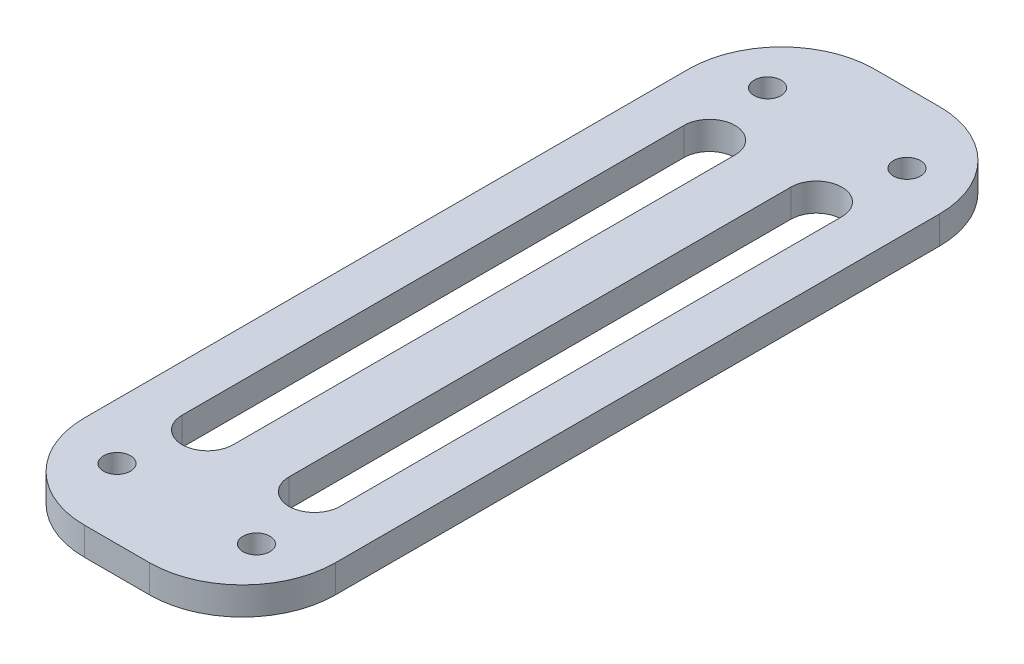
SolidWorks part; units mm, degrees
material "Thornel Mat VMA"
ref_plane "前视基准面" through (0, 0, 0) normal (0, 0, 1) x (1, 0, 0)
ref_plane "上视基准面" through (0, 0, 0) normal (0, 1, 0) x (1, 0, 0)
ref_plane "右视基准面" through (0, 0, 0) normal (1, 0, 0) x (0, 0, -1)
other "Configuration Table"
sketch "草图1" plane through (0, 0, 0) normal (0, 1, 0) x (1, 0, 0)
  line L1 (0, 0) -> (27, 0)
  line L2 (0, 0) -> (0, 85)
  line L3 (0, 85) -> (27, 85)
  line L4 (27, 0) -> (27, 85)
  dimension "D1" = 27
  dimension "D2" = 85
extrude "凸台-拉伸1" add sketch "草图1" along normal blind 3
sketch "草图2" plane through (0, 3, 0) normal (0, 1, 0) x (1, 0, 0)
  line L0 (27, 0) -> (27, 85) construction
  line L1 (0, 85) -> (27, 85) construction
  line L2 (0, 85) -> (0, 70) construction
  line L3 (0, 70) -> (27, 70) construction
  line L4 (27, 85) -> (27, 70) construction
  line L5 (0, 77.5) -> (27, 77.5) construction
  line L6 (0, 0) -> (27, 0) construction
  line L7 (0, 0) -> (0, 15) construction
  line L8 (0, 15) -> (27, 15) construction
  line L9 (27, 0) -> (27, 15) construction
  line L10 (0, 7.5) -> (27, 7.5) construction
  line L11 (13.5, 85) -> (13.5, 0) construction
  line L12 (0, 42.5) -> (27, 42.5) construction
  line L13 (0, 85) -> (0, 0) construction
  circle A2 centre (6, 7.5) radius 1.45
  circle A3 centre (21, 7.5) radius 1.45
  circle A4 centre (21, 77.5) radius 1.45
  circle A5 centre (6, 77.5) radius 1.45
  dimension "D3" = 2.9
  dimension "D4" = 6
  dimension "D1" = 15
  dimension "D2" = 15
extrude "切除-拉伸1" cut sketch "草图2" against normal through all
sketch "草图3" plane through (0, 3, 0) normal (0, 1, 0) x (1, 0, 0)
  line L0 (7.75, 69.5) -> (7.75, 15.5) construction
  line L1 (10.5, 69.5) -> (10.5, 15.5)
  line L2 (5, 69.5) -> (5, 15.5)
  line L3 (13.5, 85) -> (13.5, 0) construction
  line L4 (27, 85) -> (0, 85) construction
  line L5 (0, 0) -> (27, 0) construction
  line L6 (0, 85) -> (0, 0) construction
  line L7 (19.25, 69.5) -> (19.25, 15.5) construction
  line L8 (16.5, 69.5) -> (16.5, 15.5)
  line L9 (22, 69.5) -> (22, 15.5)
  arc A0 (10.5, 69.5) -> (5, 69.5) centre (7.75, 69.5) ccw
  arc A1 (5, 15.5) -> (10.5, 15.5) centre (7.75, 15.5) ccw
  circle A2 centre (6, 77.5) radius 1.45 construction
  circle A3 centre (6, 7.5) radius 1.45 construction
  arc A4 (16.5, 69.5) -> (22, 69.5) centre (19.25, 69.5) cw
  arc A5 (22, 15.5) -> (16.5, 15.5) centre (19.25, 15.5) cw
  point P2 (7.75, 42.5)
  point P13 (6.8462, 70.9997)
  point P14 (7.3847, 13.0772)
  point P23 (19.25, 42.5)
  dimension "D1" = 8
  dimension "D2" = 8
  dimension "D3" = 5
  dimension "D4" = 3
extrude "切除-拉伸2" cut sketch "草图3" against normal through all
fillet "圆角1" radius 10 4 edges at (0, 1.5, -85) (0, 1.5, 0) (27, 1.5, 0) (27, 1.5, -85)
